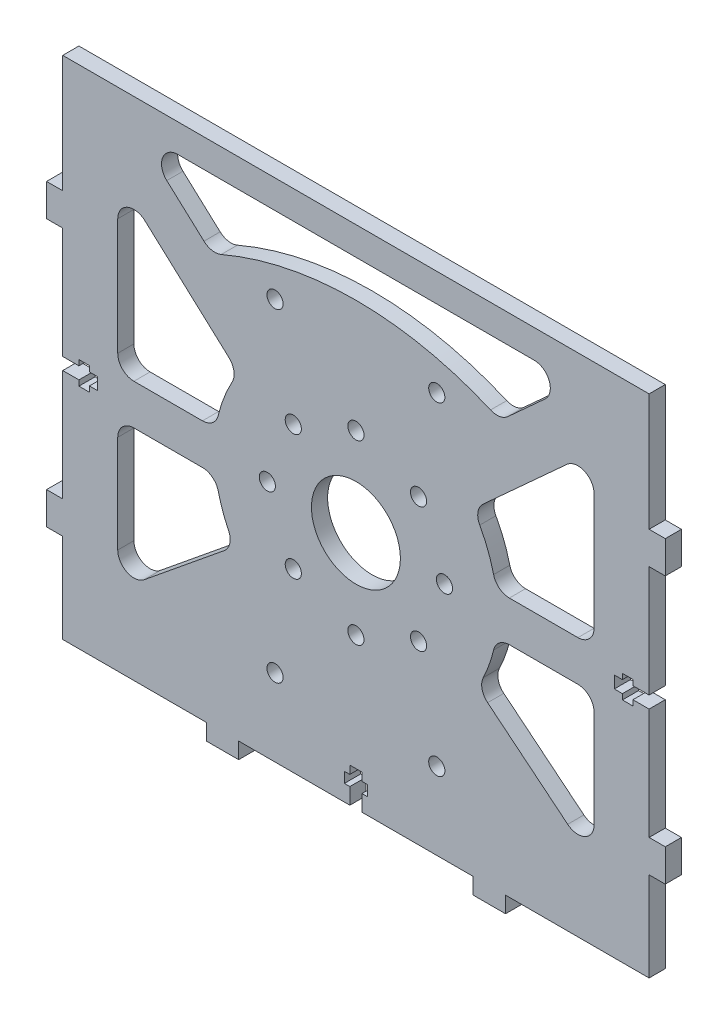
SolidWorks part; units mm, degrees
ref_plane "前视基准面" through (0, 0, 0) normal (0, 0, 1) x (1, 0, 0)
ref_plane "上视基准面" through (0, 0, 0) normal (0, 1, 0) x (1, 0, 0)
ref_plane "右视基准面" through (0, 0, 0) normal (1, 0, 0) x (0, 0, -1)
sketch "草图1" plane through (0, 0, 0) normal (0, 0, 1) x (1, 0, 0)
  line L9 (145, 64.5) -> (149, 64.5)
  line L10 (149, 64.5) -> (149, 63.15)
  line L11 (149, 63.15) -> (151.6, 63.15)
  line L12 (151.6, 63.15) -> (151.6, 64.5)
  line L13 (151.6, 64.5) -> (153.6, 64.5)
  line L14 (153.6, 64.5) -> (153.6, 67.5)
  line L23 (145, 66) -> (143.6922, 66) construction
  line L24 (145, 64.5) -> (145, 66) construction
  line L25 (151.6, 68.85) -> (151.6, 67.5)
  line L26 (149, 67.5) -> (149, 68.85)
  line L27 (151.6, 67.5) -> (153.6, 67.5)
  line L28 (149, 68.85) -> (151.6, 68.85)
  line L29 (145, 67.5) -> (149, 67.5)
  line L31 (145, 29) -> (141, 29)
  line L32 (141, 29) -> (141, 37)
  line L33 (141, 37) -> (145, 37)
  line L34 (145, 37) -> (145, 64.5)
  line L35 (141, 33) -> (142.703, 33) construction
  line L36 (145, 103) -> (141, 103)
  line L37 (145, 132) -> (145, 103)
  line L38 (141, 103) -> (141, 95)
  line L39 (141, 95) -> (145, 95)
  line L40 (145, 95) -> (145, 67.5)
  line L42 (145, 6.9) -> (145, 29)
  line L43 (294, 33) -> (292.297, 33) construction
  line L44 (290, 64.5) -> (290, 66) construction
  line L45 (290, 66) -> (291.3078, 66) construction
  line L47 (290, 95) -> (290, 67.5)
  line L48 (294, 95) -> (290, 95)
  line L49 (294, 103) -> (294, 95)
  line L50 (290, 132) -> (290, 103)
  line L51 (290, 103) -> (294, 103)
  line L52 (290, 37) -> (290, 64.5)
  line L53 (294, 37) -> (290, 37)
  line L54 (294, 29) -> (294, 37)
  line L55 (290, 29) -> (294, 29)
  line L57 (290, 67.5) -> (286, 67.5)
  line L58 (286, 68.85) -> (283.4, 68.85)
  line L59 (283.4, 67.5) -> (281.4, 67.5)
  line L60 (286, 67.5) -> (286, 68.85)
  line L61 (283.4, 68.85) -> (283.4, 67.5)
  line L62 (281.4, 64.5) -> (281.4, 67.5)
  line L63 (283.4, 64.5) -> (281.4, 64.5)
  line L64 (283.4, 63.15) -> (283.4, 64.5)
  line L65 (286, 63.15) -> (283.4, 63.15)
  line L66 (286, 64.5) -> (286, 63.15)
  line L67 (290, 64.5) -> (286, 64.5)
  line L68 (145, 132) -> (290, 132)
  line L69 (281.4, 66) -> (153.6, 66) construction
  line L70 (217.5, 6.9) -> (217.5, 25.4388) construction
  line L73 (217.5, 6.9) -> (217.5, 5.5922) construction
  line L99 (246.5, 6.9) -> (219, 6.9)
  line L100 (246.5, 2.9) -> (246.5, 6.9)
  line L101 (254.5, 2.9) -> (246.5, 2.9)
  line L102 (283.5, 6.9) -> (254.5, 6.9)
  line L103 (254.5, 6.9) -> (254.5, 2.9)
  line L104 (188.5, 6.9) -> (216, 6.9)
  line L105 (188.5, 2.9) -> (188.5, 6.9)
  line L106 (180.5, 2.9) -> (188.5, 2.9)
  line L107 (180.5, 6.9) -> (180.5, 2.9)
  line L108 (151.5, 6.9) -> (180.5, 6.9)
  line L109 (219, 6.9) -> (219, 10.9)
  line L110 (220.35, 10.9) -> (220.35, 13.5)
  line L111 (219, 13.5) -> (219, 15.5)
  line L112 (219, 10.9) -> (220.35, 10.9)
  line L113 (220.35, 13.5) -> (219, 13.5)
  line L114 (216, 15.5) -> (219, 15.5)
  line L115 (216, 13.5) -> (216, 15.5)
  line L116 (214.65, 13.5) -> (216, 13.5)
  line L117 (214.65, 10.9) -> (214.65, 13.5)
  line L118 (216, 10.9) -> (214.65, 10.9)
  line L119 (216, 6.9) -> (216, 10.9)
  line L120 (283.5, 6.9) -> (290, 6.9)
  line L121 (151.5, 6.9) -> (145, 6.9)
  line L122 (290, 29) -> (290, 6.9)
  circle A6 centre (217.5, 66) radius 21.9 construction
  circle A7 centre (217.5, 44.1) radius 2
  circle A8 centre (202.0144, 50.5144) radius 2
  circle A9 centre (195.6, 66) radius 2
  circle A10 centre (202.0144, 81.4856) radius 2
  circle A11 centre (217.5, 87.9) radius 2
  circle A12 centre (232.9856, 81.4856) radius 2
  circle A13 centre (239.4, 66) radius 2
  circle A14 centre (232.9856, 50.5144) radius 2
  circle A15 centre (217.5, 66) radius 11
  circle A19 centre (197.5, 106) radius 2
  circle A20 centre (237.5, 106) radius 2
  circle A22 centre (237.5, 26) radius 2
  circle A23 centre (197.5, 26) radius 2
  point P15 (144.3461, 66)
  dimension "D2" = 8
  dimension "D3" = 4
  dimension "D4" = 2
  dimension "D5" = 2.6
  dimension "D6" = 1.35
  dimension "D8" = 1.5
extrude "凸台-拉伸1" add sketch "草图1" along normal blind 4 contours L68 L50 L51 L49 L48 L47 L57 L60 L58 L61 L59 L62 L63 L64 L65 L66 L67 L52 L53 L54 L55 L31 L32 L33 L34 L9 L10 L11 L12 L13 L14 L27 L25 L28 L26 L29 L40 L39 L38 L36 L37
sketch "草图2" plane through (290, 0, 0) normal (1, 0, 0) x (0, 0, -1)
  line L0 (-2, 67.5) -> (-2, 64.5)
  line L1 (-4, 67.5) -> (0, 67.5) construction
  line L2 (-4, 64.5) -> (0, 64.5) construction
  circle A0 centre (-2, 66) radius 1.5
sketch "草图3" plane through (0, 0, 0) normal (0, 0, -1) x (-1, 0, 0)
  line L19 (-255.4473, 61) -> (-272.4, 61)
  line L22 (-269.7073, 106.7651) -> (-248.9271, 87.848)
  line L25 (-255.4473, 71) -> (-272.4, 71)
  line L26 (-276.4, 75) -> (-276.4, 103.8072)
  line L29 (-276.4, 57) -> (-276.4, 32.8585)
  line L30 (-158.6, 57) -> (-158.6, 32.8585)
  line L31 (-165.1274, 29.7581) -> (-184.9279, 45.8989)
  line L32 (-269.8726, 29.7581) -> (-250.0721, 45.8989)
  line L33 (-217.5, 66) -> (-217.5, 58.7222) construction
  line L34 (-179.5527, 61) -> (-162.6, 61)
  line L35 (-179.5527, 71) -> (-162.6, 71)
  line L36 (-158.6, 75) -> (-158.6, 103.8072)
  line L37 (-165.2927, 106.7651) -> (-186.0729, 87.848)
  line L38 (-241.9948, 97.7648) -> (-264.269, 118.0421) construction
  line L39 (-261.5763, 125) -> (-173.4237, 125)
  line L40 (-193.0052, 97.7648) -> (-170.731, 118.0421) construction
  line L41 (-179.9299, 109.6679) -> (-170.731, 118.0421)
  line L42 (-255.0701, 109.6679) -> (-264.269, 118.0421)
  line L52 (-191.3089, 35.6186) -> (-183.9261, 29.6004) construction
  line L54 (-248.5465, 22.5) -> (-186.4535, 22.5) construction
  line L55 (-243.6911, 35.6186) -> (-251.0739, 29.6004) construction
  circle A10 centre (-217.5, 66) radius 30 construction
  arc A11 (-251.5553, 74.0769) -> (-248.1204, 82.9526) centre (-217.5, 66) cw
  arc A13 (-269.8726, 29.7581) -> (-276.4, 32.8585) centre (-272.4, 32.8585) cw
  arc A14 (-251.5553, 57.9231) -> (-248.9996, 50.7429) centre (-217.5, 66) ccw
  arc A15 (-276.4, 57) -> (-272.4, 61) centre (-272.4, 57) cw
  arc A16 (-250.0721, 45.8989) -> (-248.9996, 50.7429) centre (-252.5995, 48.9993) ccw
  arc A17 (-251.5553, 57.9231) -> (-255.4473, 61) centre (-255.4473, 57) ccw
  arc A18 (-251.5553, 74.0769) -> (-255.4473, 71) centre (-255.4473, 75) cw
  arc A19 (-272.4, 71) -> (-276.4, 75) centre (-272.4, 75) cw
  arc A20 (-276.4, 103.8072) -> (-269.7073, 106.7651) centre (-272.4, 103.8072) cw
  arc A21 (-248.1204, 82.9526) -> (-248.9271, 87.848) centre (-251.6199, 84.8901) ccw
  arc A22 (-183.4447, 57.9231) -> (-186.0004, 50.7429) centre (-217.5, 66) cw
  arc A23 (-184.9279, 45.8989) -> (-186.0004, 50.7429) centre (-182.4005, 48.9993) cw
  arc A24 (-183.4447, 57.9231) -> (-179.5527, 61) centre (-179.5527, 57) cw
  arc A25 (-165.1274, 29.7581) -> (-158.6, 32.8585) centre (-162.6, 32.8585) ccw
  arc A26 (-158.6, 57) -> (-162.6, 61) centre (-162.6, 57) ccw
  arc A27 (-183.4447, 74.0769) -> (-179.5527, 71) centre (-179.5527, 75) ccw
  arc A28 (-186.8796, 82.9526) -> (-186.0729, 87.848) centre (-183.3801, 84.8901) cw
  arc A29 (-158.6, 103.8072) -> (-165.2927, 106.7651) centre (-162.6, 103.8072) ccw
  arc A30 (-162.6, 71) -> (-158.6, 75) centre (-162.6, 75) ccw
  arc A31 (-183.4447, 74.0769) -> (-186.8796, 82.9526) centre (-217.5, 66) ccw
  arc A33 (-237.175, 97.3352) -> (-197.825, 97.3352) centre (-217.5, 66) cw construction
  arc A34 (-186.4535, 22.5) -> (-183.9261, 29.6004) centre (-186.4535, 26.5) ccw construction
  arc A35 (-197.825, 97.3352) -> (-193.0052, 97.7648) centre (-195.6979, 100.7228) ccw construction
  arc A36 (-237.175, 97.3352) -> (-241.9948, 97.7648) centre (-239.3021, 100.7228) cw construction
  arc A37 (-264.269, 118.0421) -> (-261.5763, 125) centre (-261.5763, 121) cw
  arc A38 (-170.731, 118.0421) -> (-173.4237, 125) centre (-173.4237, 121) ccw
  arc A40 (-238.8551, 35.7848) -> (-196.1449, 35.7848) centre (-217.5, 66) ccw construction
  arc A41 (-191.3089, 35.6186) -> (-196.1449, 35.7848) centre (-193.8363, 32.5182) ccw construction
  arc A42 (-248.5465, 22.5) -> (-251.0739, 29.6004) centre (-248.5465, 26.5) cw construction
  arc A43 (-243.6911, 35.6186) -> (-238.8551, 35.7848) centre (-241.1637, 32.5182) cw construction
  arc A44 (-184.2046, 108.952) -> (-250.7954, 108.952) centre (-217.5, 31.629) ccw
  arc A45 (-184.2046, 108.952) -> (-179.9299, 109.6679) centre (-182.6226, 112.6258) ccw
  arc A46 (-255.0701, 109.6679) -> (-250.7954, 108.952) centre (-252.3774, 112.6258) ccw
  point P83 (-181.8681, 107.9035)
  point P87 (-253.1319, 107.9035)
  dimension "D4" = 4
  dimension "D1" = 4
  dimension "D3" = 4
  dimension "D2" = 4
extrude "切除-拉伸2" cut sketch "草图3" against normal blind 4
sketch "草图4" plane through (145, 0, 0) normal (-1, 0, 0) x (0, 0, 1)
  line L0 (2, 67.5) -> (2, 64.5)
  line L1 (4, 67.5) -> (0, 67.5) construction
  line L2 (4, 64.5) -> (0, 64.5) construction
  circle A0 centre (2, 66) radius 1.5
